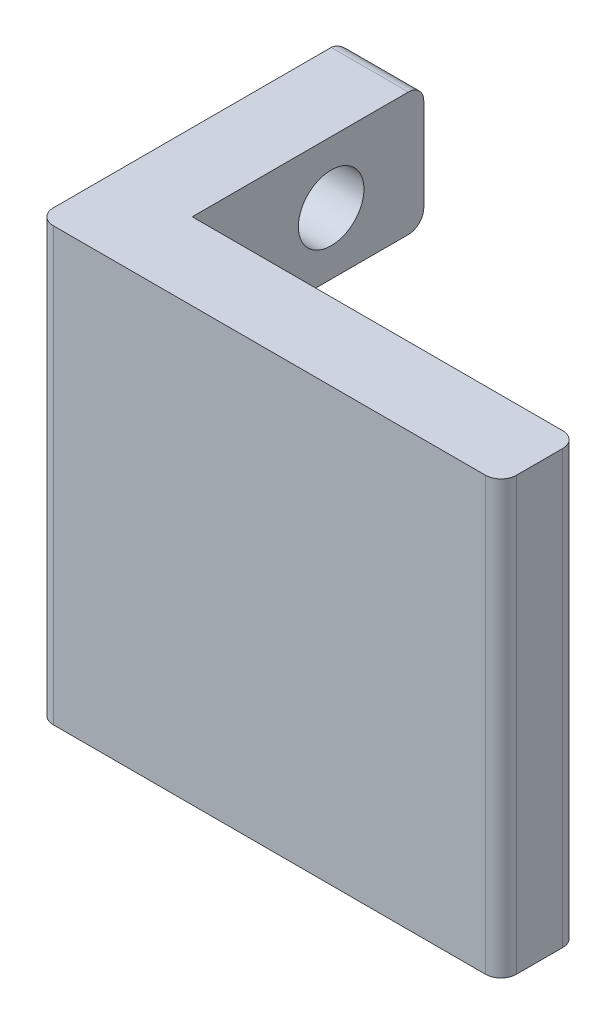
SolidWorks part; units mm, degrees
ref_plane "Front Plane" through (0, 0, 0) normal (0, 0, 1) x (1, 0, 0)
ref_plane "Top Plane" through (0, 0, 0) normal (0, 1, 0) x (1, 0, 0)
ref_plane "Right Plane" through (0, 0, 0) normal (1, 0, 0) x (0, 0, -1)
sketch "Sketch1" plane through (0, 0, 0) normal (0, 1, 0) x (1, 0, 0)
  line L1 (-12.5, 2.5) -> (12.5, 2.5)
  line L2 (-12.5, 2.5) -> (-12.5, -2.5)
  line L3 (-12.5, -2.5) -> (12.5, -2.5)
  line L4 (12.5, 2.5) -> (12.5, -2.5)
  line L5 (-12.5, 2.5) -> (12.5, -2.5) construction
  line L6 (-12.5, -2.5) -> (12.5, 2.5) construction
  point P0 (0, 0)
  dimension "D1" = 25
  dimension "D2" = 5
extrude "Boss-Extrude1" add sketch "Sketch1" along normal blind 28
sketch "Sketch4" plane through (-12.5, 0, 0) normal (-1, 0, 0) x (0, 0, 1)
  line L0 (-17.5, 20) -> (-2.5, 20)
  line L1 (2.5, 28) -> (-17.5, 28)
  line L2 (2.5, 28) -> (2.5, 0)
  line L3 (2.5, 0) -> (-17.5, 0)
  line L4 (-17.5, 28) -> (-17.5, 20)
  line L5 (-2.5, 28) -> (-2.5, 0) construction
  line L6 (-17.5, 8) -> (-2.5, 8)
  line L7 (-2.5, 20) -> (-2.5, 8)
  line L8 (-17.5, 8) -> (-17.5, 0)
  dimension "D1" = 28
  dimension "D2" = 20
  dimension "D3" = 8
  dimension "D4" = 8
extrude "Boss-Extrude3" add sketch "Sketch4" along normal blind 5
fillet "Fillet2" radius 1 14 edges at (-17.5, 4, -17.5) (-17.5, 24, -17.5) (-17.5, 14, 2.5) (12.5, 14, 2.5) (-17.5, 14, -2.5) (-15, 0, -17.5) (-15, 8, -17.5) (-15, 28, -17.5) (-15, 20, -17.5) (-17.5, 8, -10) (-17.5, 20, -10) (-15, 8, -2.5) (-15, 20, -2.5) (12.5, 14, -2.5)
sketch "Sketch5" plane through (-17.5, 0, 0) normal (-1, 0, 0) x (0, 0, 1)
  line L0 (1.5, 28) -> (-16.5, 28) construction
  line L1 (-2.5, 8) -> (-16.5, 8) construction
  line L2 (-2.5, 20) -> (-2.5, 8) construction
  circle A0 centre (-11.5, 24) radius 2.125
  circle A1 centre (-11.5, 4) radius 2.125
  dimension "D5" = 4.25
  dimension "D6" = 4.25
  dimension "D1" = 4
  dimension "D2" = 4
  dimension "D3" = 9
  dimension "D4" = 9
extrude "Cut-Extrude2" cut sketch "Sketch5" against normal up to next
